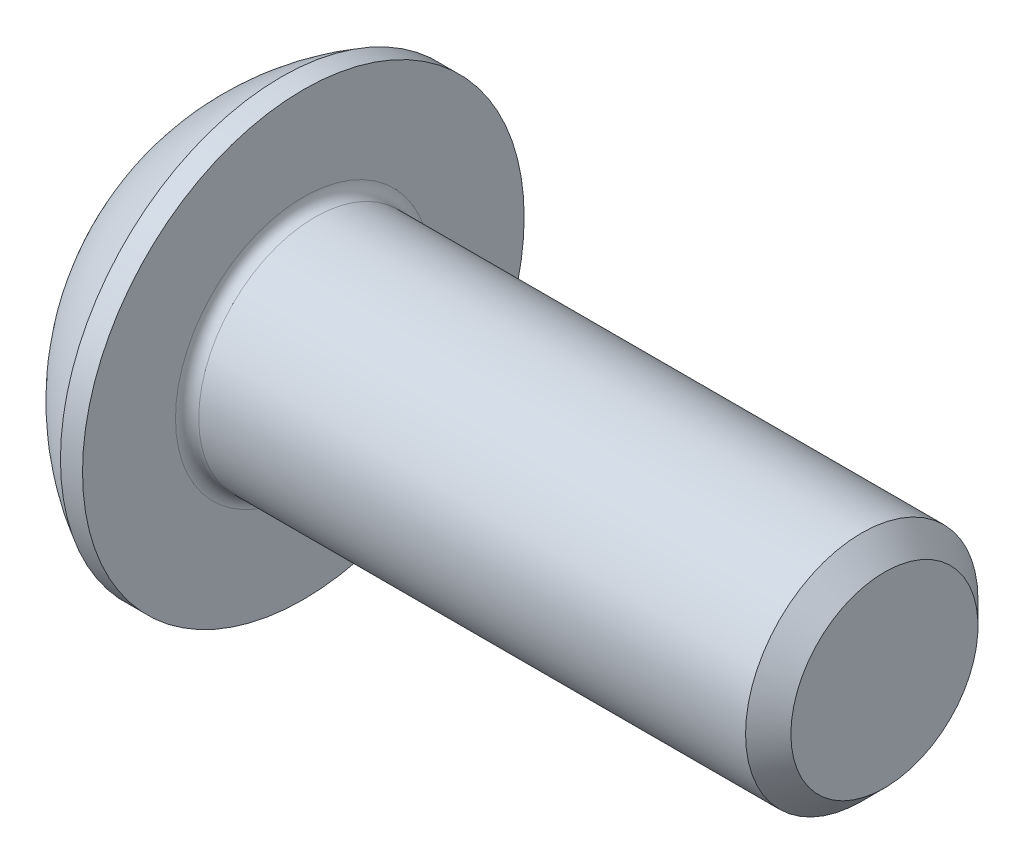
SolidWorks part; units mm, degrees
ref_plane "Plane1" through (0, 0, 0) normal (0, 0, 1) x (1, 0, 0)
ref_plane "Plane2" through (0, 0, 0) normal (0, 1, 0) x (1, 0, 0)
ref_plane "Plane3" through (0, 0, 0) normal (1, 0, 0) x (0, 0, -1)
sketch "BodySke" plane through (0, 0, 0) normal (0, 0, 1) x (1, 0, 0)
  line L0 (12.2, 0) -> (12.2, 1.61)
  line L1 (11.81, 2) -> (2.2, 2)
  line L2 (2.2, 2) -> (2.2, 3.8)
  line L3 (2.2, 3.8) -> (1.82, 3.8)
  line L4 (0, 0) -> (101.6, 0) construction
  line L5 (2.2, -3.8) -> (1.82, -3.8) construction
  line L6 (55.6768, -2) -> (2.2, -2) construction
  line L7 (12.2, 0) -> (0, 0)
  line L8 (0, 1.9) -> (0, -1.9) construction
  line L9 (0, 0) -> (0, 1.9)
  line L10 (12.2, 1.61) -> (11.81, 2)
  line L11 (12.2, -1.61) -> (11.81, -2) construction
  line L12 (2.9, 9.525) -> (2.9, -2) construction
  line L13 (2.2, 9.525) -> (2.2, -2) construction
  arc A1 (0, 1.9) -> (1.82, 3.8) centre (3.8853, 0) cw
  dimension "D1" = 3.8
  dimension "Diameter" = 4
  dimension "Length" = 10
  dimension "Head_dia" = 7.6
  dimension "Head_ht" = 2.2
  dimension "Head_side_ht" = 0.38
  dimension "Minor_dia" = 3.22
  dimension "Body_ch_ang" = 45
  dimension "Advance" = 0.7
  dimension "Thread_nom" = 10
revolve "BaseBody" add sketch "BodySke" angle 360 about L4
cosmetic thread "ThreadCosmetic" [suppressed] parameters "Thread_length"=8.6, "Thread_minor"=3.22
fillet "Fillet1" radius 0.2 1 edges at (2.2, 0, 2)
sketch "Sketch2" plane through (0, 0, 0) normal (0, 0, 1) x (1, 0, 0)
  line L0 (0, 1.25) -> (1.3, 1.25)
  line L1 (1.3, 1.25) -> (2.0217, 0)
  line L3 (2.0217, 0) -> (0, 0)
  line L4 (0, 0) -> (0, 1.25)
  line L5 (0, -1.25) -> (1.3, -1.25) construction
  line L6 (0, 0) -> (47.625, 0) construction
  dimension "D2" = 60
  dimension "PreBroach_depth" = 1.3
  dimension "PreBroach_dia" = 2.5
revolve "PreBroach" cut sketch "Sketch2" angle 360 about L6
sketch "Sketch3" plane through (0, 0, 0) normal (1, 0, 0) x (0, 0, -1)
  line L0 (-1.25, -0.7217) -> (-1.25, 0.7217)
  line L1 (-1.25, 0.7217) -> (0, 1.4434)
  line L2 (0, 1.4434) -> (1.25, 0.7217)
  line L3 (1.25, 0.7217) -> (1.25, -0.7217)
  line L4 (1.25, -0.7217) -> (0, -1.4434)
  line L5 (0, -1.4434) -> (-1.25, -0.7217)
  dimension "D1" = 1.25
  dimension "D2" = 1.25
  dimension "D3" = 2.5
  dimension "Hex_size" = 2.5
extrude "Hex" cut sketch "Sketch3" along normal blind 1.3
sketch "ThdSchSke" plane through (0, 0, 0) normal (0, 0, 1) x (1, 0, 0)
  line L0 (3.6, -1.61) -> (3.3269, -2)
  line L1 (3.6, -1.61) -> (3.8731, -2)
  line L2 (3.8731, -2) -> (3.8731, -2.5)
  line L3 (-3.175, 0) -> (5.1513, 0) construction
  line L5 (3.8731, -2.5) -> (3.3269, -2.5)
  line L6 (3.3269, -2.5) -> (3.3269, -2)
  dimension "Thread_minor" = 3.22
  dimension "Diameter" = 4
  dimension "Start" = 3.6
  dimension "SideAngle" = 55
  dimension "VeeAngle" = 70
  dimension "Overcut" = 5
revolve "ThreadSchematic" [suppressed] cut sketch "ThdSchSke" angle 360 about L3
pattern_linear "ThdSchPat" [suppressed]
equation "\"D1@BodySke\" = \"Head_dia@BodySke\" * .5"
equation "\"Thread_minor@ThreadCosmetic\" = \"Minor_dia@BodySke\""
equation "\"D1@Sketch3\" = \"Hex_size@Sketch3\" / 2"
equation "\"D2@Sketch3\" = \"D1@Sketch3\""
equation "\"D3@Sketch3\" = \"Hex_size@Sketch3\""
equation "\"Thread_length@ThreadCosmetic\" = ((sgn( (\"Length@BodySke\" - \"Advance@BodySke\" * 2.0) - \"Thread_nom@BodySke\" )-1)*( (\"Length@BodySke\" - \"Advance@BodySke\" * 2.0) - \"Thread_nom@BodySke\" ))/-2+ \"Thread_nom@BodySke\""
equation "\"Thread_minor@ThdSchSke\" = \"Minor_dia@BodySke\""
equation "\"Diameter@ThdSchSke\" = \"Diameter@BodySke\""
equation "\"Overcut@ThdSchSke\" = \"Diameter@BodySke\" * 1.25"
equation "\"Start@ThdSchSke\" = \"Head_ht@BodySke\" + \"Length@BodySke\" - \"Thread_length@ThreadCosmetic\"  '---Non-countersunk---"
equation "\"Num_threads@ThdSchPat\" = int( \"Thread_length@ThreadCosmetic\" / \"Advance@BodySke\" + 0.999 )  + 1"
equation "\"Advance@ThdSchPat\" = \"Thread_length@ThreadCosmetic\" /  (\"Num_threads@ThdSchPat\" - 1) 'relax it"
equation "\"Num_threads@ThdSchPat\" = \"Num_threads@ThdSchPat\" - sgn( \"Num_threads@ThdSchPat\" - 1) '---chamfered tips only---"
